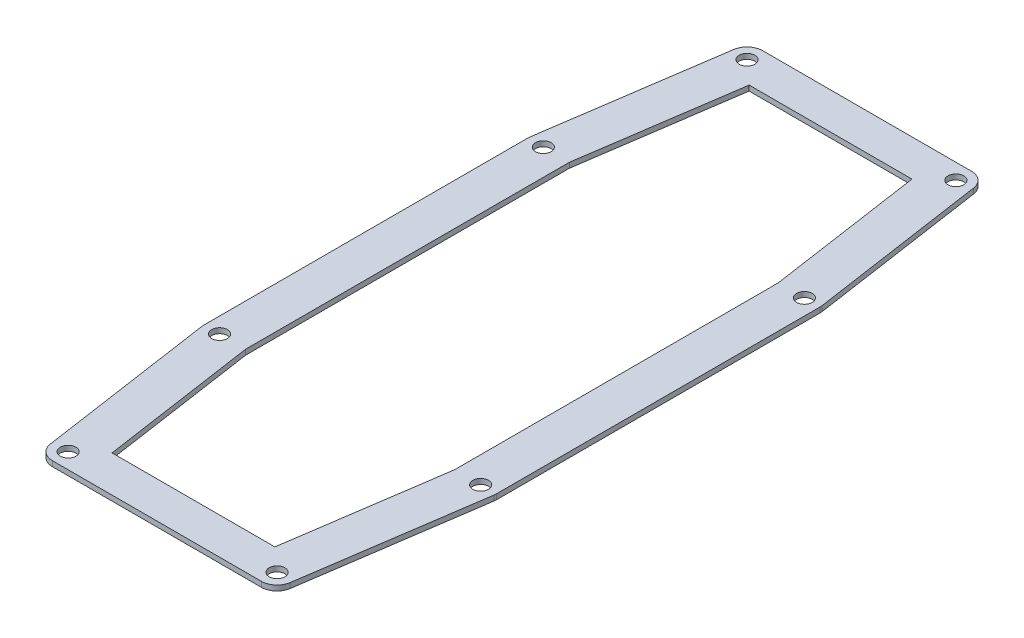
SolidWorks part; units mm, degrees
ref_plane "前视基准面" through (0, 0, 0) normal (0, 0, 1) x (1, 0, 0)
ref_plane "上视基准面" through (0, 0, 0) normal (0, 1, 0) x (1, 0, 0)
ref_plane "右视基准面" through (0, 0, 0) normal (1, 0, 0) x (0, 0, -1)
sketch "草图1" plane through (0, 0, 0) normal (0, 1, 0) x (1, 0, 0)
  line L0 (5, 99) -> (45, 99)
  line L1 (0, 0) -> (50, 0) construction
  line L2 (0, 0) -> (0, 62) construction
  line L3 (0, 62) -> (50, 62) construction
  line L4 (50, 0) -> (50, 62) construction
  line L5 (5, 96) -> (45, 96) construction
  line L6 (5, 96) -> (5, -34) construction
  line L7 (5, -34) -> (45, -34) construction
  line L8 (45, 96) -> (45, -34) construction
  line L9 (2.0319, 96.4365) -> (-2.9681, 62.4365)
  line L10 (-3, 62) -> (-3, 0)
  line L11 (-2.9681, -0.4365) -> (2.0319, -34.4365)
  line L12 (5, -37) -> (45, -37)
  line L13 (25, 62) -> (25, 0) construction
  line L14 (52.9681, -0.4365) -> (47.9681, -34.4365)
  line L15 (53, 62) -> (53, 0)
  line L16 (47.9681, 96.4365) -> (52.9681, 62.4365)
  line L17 (9.4118, 92) -> (5, 62)
  line L18 (5, 62) -> (5, 0)
  line L19 (5, 0) -> (9.4118, -30)
  line L20 (9.4118, -30) -> (40.5882, -30)
  line L21 (9.4118, 92) -> (40.5882, 92)
  line L22 (45, 0) -> (40.5882, -30)
  line L23 (45, 62) -> (45, 0)
  line L24 (40.5882, 92) -> (45, 62)
  circle A0 centre (0, 62) radius 1.5
  circle A1 centre (50, 62) radius 1.5
  circle A2 centre (0, 0) radius 1.5
  circle A3 centre (50, 0) radius 1.5
  circle A4 centre (5, 96) radius 1.5
  circle A5 centre (45, 96) radius 1.5
  circle A6 centre (5, -34) radius 1.5
  circle A7 centre (45, -34) radius 1.5
  arc A8 (5, 99) -> (2.0319, 96.4365) centre (5, 96) ccw
  arc A9 (2.0319, -34.4365) -> (5, -37) centre (5, -34) ccw
  arc A10 (-3, 0) -> (-2.9681, -0.4365) centre (0, 0) ccw
  arc A11 (-2.9681, 62.4365) -> (-3, 62) centre (0, 62) ccw
  arc A12 (47.9681, -34.4365) -> (45, -37) centre (45, -34) cw
  arc A13 (53, 0) -> (52.9681, -0.4365) centre (50, 0) cw
  arc A14 (52.9681, 62.4365) -> (53, 62) centre (50, 62) cw
  arc A15 (45, 99) -> (47.9681, 96.4365) centre (45, 96) cw
  dimension "D3" = 3
  dimension "D8" = 3
  dimension "D9" = 3
  dimension "D10" = 3
  dimension "D11" = 3
  dimension "D1" = 50
  dimension "D2" = 62
  dimension "D4" = 5
  dimension "D5" = 7
  dimension "D6" = 34
  dimension "D7" = 34
  dimension "D12" = 7
extrude "凸台-拉伸1" add sketch "草图1" along normal blind 1
